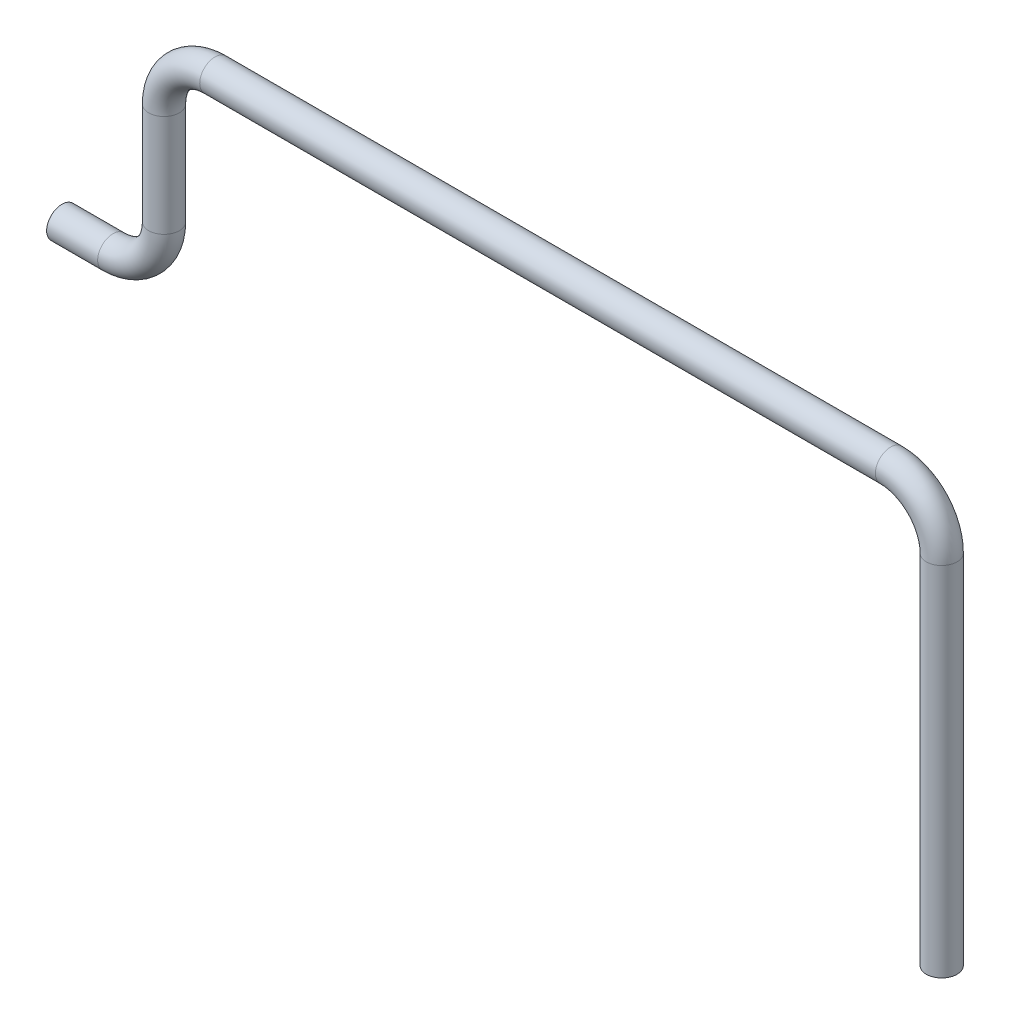
SolidWorks part; units mm, degrees
ref_plane "Front Plane" through (0, 0, 0) normal (0, 0, 1) x (1, 0, 0)
ref_plane "Top Plane" through (0, 0, 0) normal (0, 1, 0) x (1, 0, 0)
ref_plane "Right Plane" through (0, 0, 0) normal (1, 0, 0) x (0, 0, -1)
sketch "Sketch1" plane through (0, 0, 0) normal (0, 0, 1) x (1, 0, 0)
  line L0 (0, 0) -> (5, 0)
  line L1 (86.2, 15) -> (86.2, -20)
  line L2 (81.2, 20) -> (15, 20)
  line L3 (10, 15) -> (10, 5)
  arc A0 (81.2, 20) -> (86.2, 15) centre (81.2, 15) cw
  arc A1 (10, 15) -> (15, 20) centre (15, 15) cw
  arc A2 (10, 5) -> (5, 0) centre (5, 5) cw
  point P8 (180, 20)
  point P11 (10, 20)
  point P14 (10, 0)
  dimension "D5" = 5
  dimension "D1" = 20
  dimension "D2" = 40
  dimension "D3" = 76.2
  dimension "D4" = 10
sweep "Sweep1" add path "Sketch1" circular profile diameter 3 parameters "D3"=3
